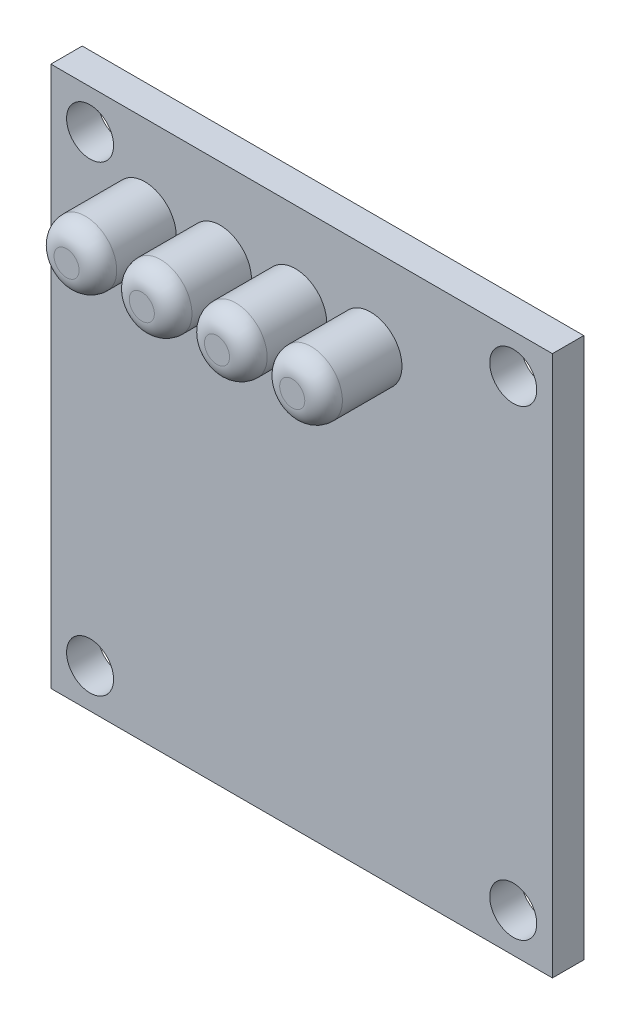
SolidWorks part; units mm, degrees
ref_plane "Front Plane" through (0, 0, 0) normal (0, 0, 1) x (1, 0, 0)
ref_plane "Top Plane" through (0, 0, 0) normal (0, 1, 0) x (1, 0, 0)
ref_plane "Right Plane" through (0, 0, 0) normal (1, 0, 0) x (0, 0, -1)
sketch "Sketch1" plane through (0, 0, 0) normal (0, 0, 1) x (1, 0, 0)
  line L1 (16, -17.25) -> (-16, -17.25)
  line L2 (16, -17.25) -> (16, 17.25)
  line L3 (16, 17.25) -> (-16, 17.25)
  line L4 (-16, -17.25) -> (-16, 17.25)
  line L5 (16, -17.25) -> (-16, 17.25) construction
  line L6 (16, 17.25) -> (-16, -17.25) construction
  circle A0 centre (-13.5, 14.75) radius 1.5
  circle A1 centre (13.5, 14.75) radius 1.5
  circle A2 centre (-13.5, -14.75) radius 1.5
  circle A3 centre (13.5, -14.75) radius 1.5
  point P0 (0, 0)
  dimension "D5" = 3
  dimension "D6" = 3
  dimension "D7" = 3
  dimension "D8" = 3
  dimension "D1" = 32
  dimension "D2" = 34.5
  dimension "D3" = 2.5
  dimension "D4" = 2.5
  dimension "D9" = 2.5
  dimension "D10" = 2.5
  dimension "D11" = 2.5
  dimension "D12" = 2.5
  dimension "D13" = 2.5
  dimension "D14" = 2.5
extrude "Boss-Extrude1" add sketch "Sketch1" along normal blind 2
sketch "Sketch2" plane through (0, 0, 2) normal (0, 0, 1) x (1, 0, 0)
  circle A0 centre (-10, 11.75) radius 2
  circle A1 centre (-13.5, 14.75) radius 1.5 construction
  circle A2 centre (-5.2, 11.75) radius 2
  circle A3 centre (-0.4, 11.75) radius 2
  circle A4 centre (4.4, 11.75) radius 2
  dimension "D2" = 4
  dimension "D1" = 3.5
  dimension "D3" = 3
  dimension "D4" = 4
extrude "Boss-Extrude2" add sketch "Sketch2" along normal blind 5
fillet "Fillet1" radius 1.2 4 edges at (6.4, 11.75, 7) (1.6, 11.75, 7) (-3.2, 11.75, 7) (-8, 11.75, 7)
